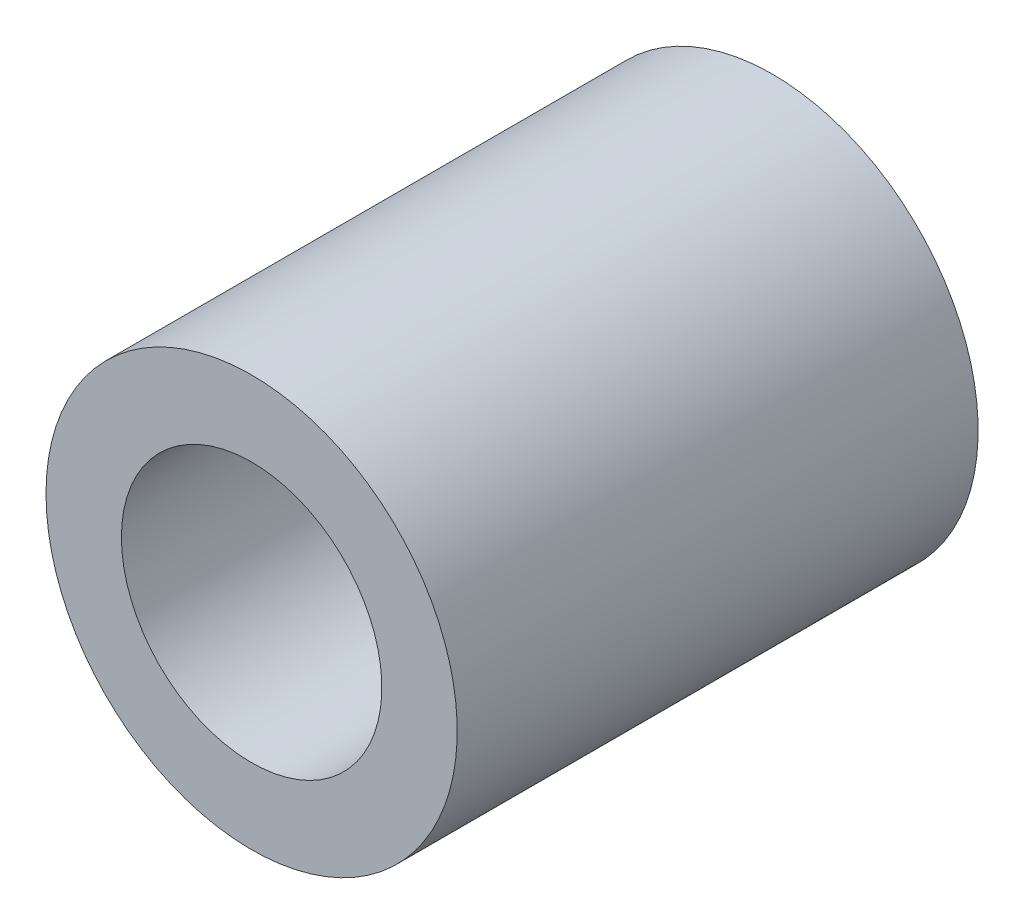
SolidWorks part; units mm, degrees
ref_plane "Alzado" through (0, 0, 0) normal (0, 0, 1) x (1, 0, 0)
ref_plane "Planta" through (0, 0, 0) normal (0, 1, 0) x (1, 0, 0)
ref_plane "Vista lateral" through (0, 0, 0) normal (1, 0, 0) x (0, 0, -1)
sketch "Croquis1" plane through (0, 0, 0) normal (0, 0, 1) x (1, 0, 0)
  circle A0 centre (0, 0) radius 3
  circle A1 centre (0, 0) radius 1.9
  dimension "D1" = 6
  dimension "D2" = 3.8
extrude "Saliente-Extruir1" add sketch "Croquis1" along normal blind 7.6
sketch "Croquis2" plane through (0, 0, 7.6) normal (0, 0, 1) x (1, 0, 0)
  line L1 (0.3834, 2.4903) -> (-0.2175, 2.4903)
  line L2 (0.3834, 2.4903) -> (0.3834, 2.9921)
  line L3 (0.3834, 2.9921) -> (-0.2175, 2.9921)
  line L4 (-0.2175, 2.4903) -> (-0.2175, 2.9921)
  circle A0 centre (0, 0) radius 3 construction
